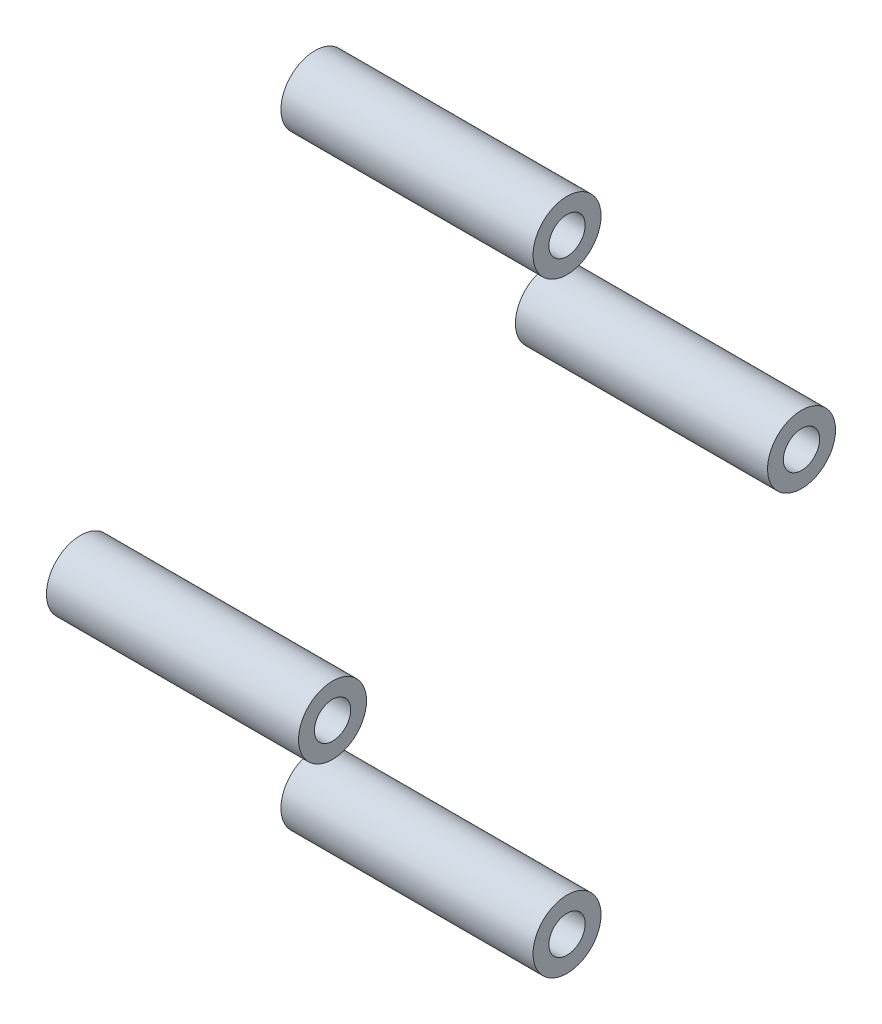
SolidWorks part; units mm, degrees
ref_plane "Front Plane" through (0, 0, 0) normal (1, 0, 0) x (0, 1, 0)
ref_plane "Top Plane" through (0, 0, 0) normal (0, 0, 1) x (0, 1, 0)
ref_plane "Right Plane" through (0, 0, 0) normal (0, 1, 0) x (-1, 0, 0)
sketch "Sketch1" plane through (0, 0, 0) normal (1, 0, 0) x (0, 1, 0)
  line L0 (746.1621, 790.3348) -> (811.4821, 790.3348) construction
  dimension "D1" = 65.32
sketch "Sketch3" plane through (0, 0, 0) normal (1, 0, 0) x (0, 1, 0)
  line L0 (-30, 0) -> (30, 0) construction
  line L1 (0, 23.25) -> (0, -23.25) construction
  circle A0 centre (0, 23.25) radius 1.8
  circle A1 centre (-30, 0) radius 1.8
  circle A2 centre (0, -23.25) radius 1.8
  circle A3 centre (30, 0) radius 1.8
  circle A4 centre (0, 23.25) radius 3.37
  circle A5 centre (30, 0) radius 3.37
  circle A6 centre (0, -23.25) radius 3.37
  circle A7 centre (-30, 0) radius 3.37
  dimension "D3" = 3.6
  dimension "D4" = 3.6
  dimension "D5" = 3.6
  dimension "D6" = 3.6
  dimension "D8" = 1.57
  dimension "D1" = 60
  dimension "D2" = 46.5
  dimension "D7" = 60
extrude "Boss-Extrude1" add sketch "Sketch3" along normal blind 25
